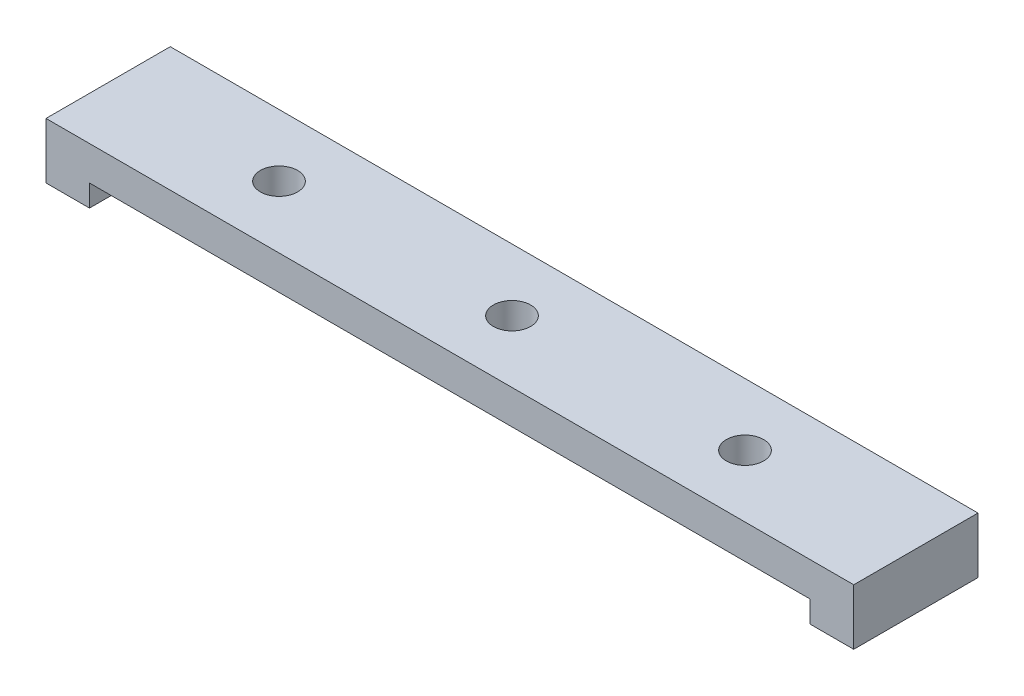
SolidWorks part; units mm, degrees
material "1060 Alloy"
ref_plane "Front Plane" through (0, 0, 0) normal (0, 0, 1) x (1, 0, 0)
ref_plane "Top Plane" through (0, 0, 0) normal (0, 1, 0) x (1, 0, 0)
ref_plane "Right Plane" through (0, 0, 0) normal (1, 0, 0) x (0, 0, -1)
sketch "Sketch1" plane through (0, 0, 0) normal (0, 1, 0) x (1, 0, 0)
  line L0 (32.5, 5) -> (32.5, 10) construction
  line L1 (0, 0) -> (65, 0)
  line L2 (0, 0) -> (0, 10)
  line L3 (0, 10) -> (65, 10)
  line L4 (65, 0) -> (65, 10)
  circle A0 centre (13.75, 5) radius 1.5
  circle A1 centre (32.5, 5) radius 1.5
  circle A2 centre (51.25, 5) radius 1.5
  dimension "D3" = 3
  dimension "D4" = 5
  dimension "D5" = 18.75
  dimension "D1" = 10
  dimension "D2" = 65
  dimension "D6" = 18.75
extrude "Boss-Extrude1" add sketch "Sketch1" along normal blind 4.5
sketch "Sketch2" plane through (0, 0, 0) normal (0, -1, 0) x (1, 0, 0)
  line L0 (0, 0) -> (65, 0) construction
  line L1 (3.5, 0) -> (61.5, 0)
  line L2 (3.5, 0) -> (3.5, -10)
  line L3 (3.5, -10) -> (61.5, -10)
  line L4 (61.5, 0) -> (61.5, -10)
  line L5 (65, -10) -> (0, -10) construction
  line L6 (0, -10) -> (0, 0) construction
  line L7 (65, 0) -> (65, -10) construction
  dimension "D1" = 3.5
  dimension "D2" = 3.5
extrude "Cut-Extrude1" cut sketch "Sketch2" against normal offset from surface (1.75 mm away) 2.75 up to face at (32.5, 4.5, -3.5)
